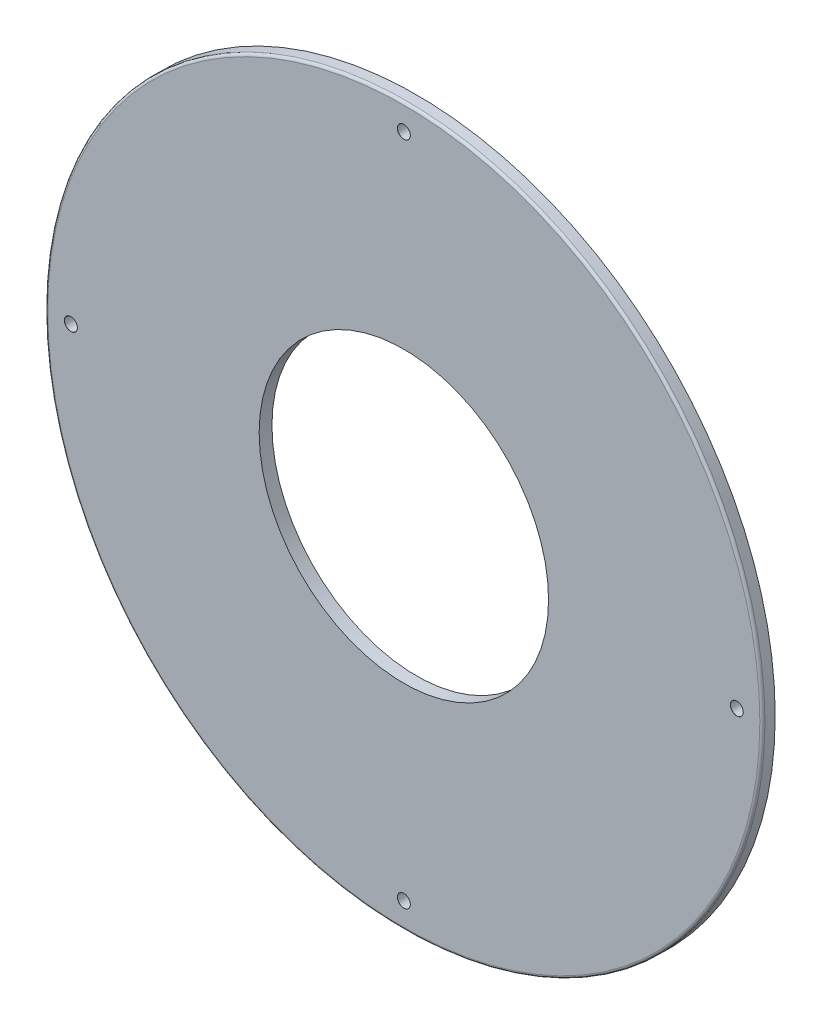
SolidWorks part; units mm, degrees
material "Gray Cast Iron"
ref_plane "Front Plane" through (0, 0, 0) normal (0, 0, 1) x (1, 0, 0)
ref_plane "Top Plane" through (0, 0, 0) normal (0, 1, 0) x (1, 0, 0)
ref_plane "Right Plane" through (0, 0, 0) normal (1, 0, 0) x (0, 0, -1)
sketch "Sketch1" plane through (0, 0, 0) normal (0, 0, 1) x (1, 0, 0)
  circle A0 centre (0, 0) radius 140
  circle A1 centre (0, 0) radius 56.5
  dimension "D1" = 280
  dimension "D2" = 113
extrude "Boss-Extrude1" add sketch "Sketch1" along normal blind 5
hole_wizard "Ø5.0mm Dowel Hole1" positions "Sketch2" profile "Sketch3" hole size "Ø5.0" standard "ISO"
sketch "Sketch2" plane through (0, 0, 5) normal (0, 0, 1) x (1, 0, 0)
  point P0 (0, 130)
  point P2 (0, -130)
  point P4 (130, 0)
  point P6 (-130, 0)
  point P9 (0, 0)
  point P10 (0, 0)
sketch "Sketch3" plane through (0, 130, 5) normal (1, 0, 0) x (0, -1, 0)
  line L0 (0, 0) -> (0, 6.5012)
  line L1 (0, 6.5012) -> (2.5, 4.999)
  line L2 (2.5, 4.999) -> (2.5, 0.025)
  line L3 (2.5, 0.025) -> (2.525, 0)
  line L5 (2.525, 0) -> (0, 0)
  line L6 (-2.5, 0.025) -> (-2.525, 0) construction
  line L10 (0, 6.5012) -> (-2.5, 4.999) construction
  line L11 (0, -6.35) -> (0, 10.1773) construction
  point P5 (0, 10.1773)
  dimension "Hole Dia." = 5
  dimension "Hole Depth" = 4.999
  dimension "Near C'Sink Dia." = 5.05
  dimension "Near C'Sink Angle" = 90
  dimension "Drill Angle" = 118
fillet "Fillet1" radius 1 1 edges at (140, 0, 5)
chamfer "Chamfer1" distance 1 angle 45 4 edges at (132.5, 0, 0) (2.5, -130, 0) (-127.5, 0, 0) (2.5, 130, 0)
